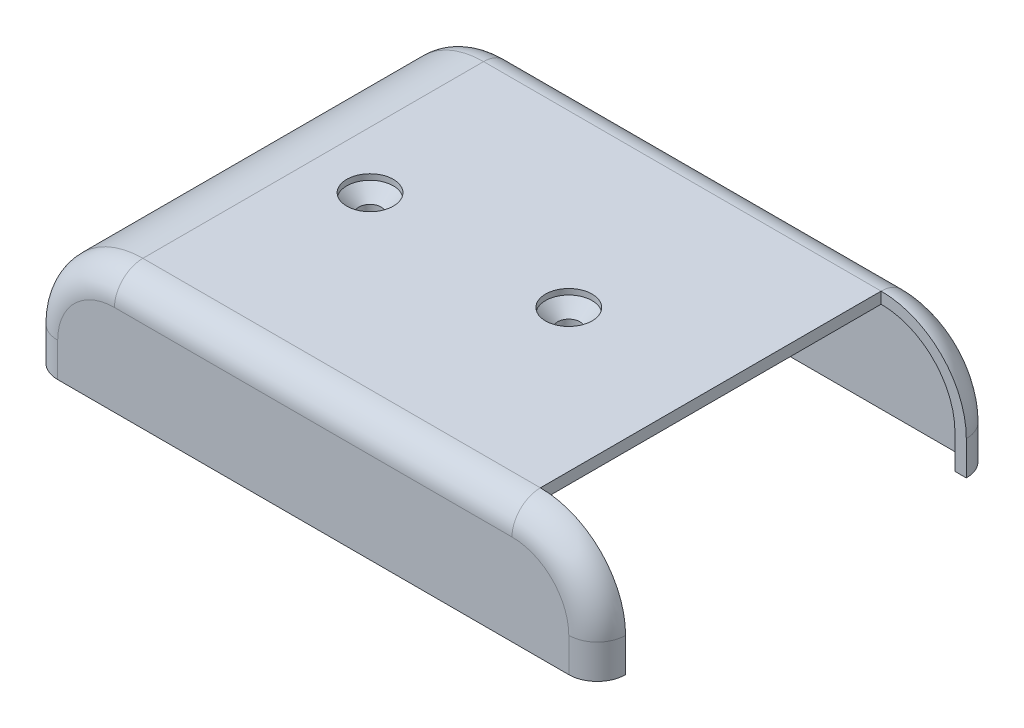
SolidWorks part; units mm, degrees
ref_plane "Front Plane" through (0, 0, 0) normal (0, 0, 1) x (1, 0, 0)
ref_plane "Top Plane" through (0, 0, 0) normal (0, 1, 0) x (1, 0, 0)
ref_plane "Right Plane" through (0, 0, 0) normal (1, 0, 0) x (0, 0, -1)
sketch "Sketch1" plane through (0, 0, 0) normal (0, 1, 0) x (1, 0, 0)
  line L1 (-50, 35) -> (50, 35)
  line L2 (-50, 35) -> (-50, -35)
  line L3 (-50, -35) -> (50, -35)
  line L4 (50, 35) -> (50, -35)
  line L5 (0, -35) -> (0, 35) construction
  line L6 (-50, 0) -> (50, 0) construction
  point P0 (0, 0)
  dimension "D1" = 70
  dimension "D2" = 100
extrude "Boss-Extrude1" add sketch "Sketch1" along normal blind 21
fillet "Fillet1" radius 15 2 edges at (50, 21, 0) (-50, 21, 0)
fillet "Fillet2" radius 5 10 edges at (50, 3, -35) (45.6066, 16.6066, -35) (-50, 3, -35) (-45.6066, 16.6066, -35) (-50, 3, 35) (-45.6066, 16.6066, 35) (50, 3, 35) (45.6066, 16.6066, 35) (0, 21, -35) (0, 21, 35)
shell "Shell1" thickness 2
sketch "Sketch2" plane through (0, 21, 0) normal (0, 1, 0) x (1, 0, 0)
  line L0 (35, 30) -> (35, -30)
  line L1 (35, -30) -> (69.0755, -30)
  line L2 (69.0755, -30) -> (69.0755, 30)
  line L3 (69.0755, 30) -> (35, 30)
extrude "Cut-Extrude1" cut sketch "Sketch2" against normal blind 45
ref_plane "Plane1" through (0, 6, 0) normal (0, 1, 0) x (1, 0, 0)
sketch "Sketch4" plane through (0, 6, 0) normal (0, 1, 0) x (1, 0, 0)
  line L0 (-50, -30) -> (-50, 30) construction
  circle A0 centre (-25, 0) radius 3
  circle A1 centre (10, 0) radius 3
  point P2 (0, 0)
  point P8 (0, 0)
  point P9 (0, 0)
  dimension "D1" = 6
  dimension "D2" = 35
  dimension "D3" = 25
extrude "Boss-Extrude2" add sketch "Sketch4" along normal up to next draft 5 draft outward yes
hole_wizard "CSK for M10 Flat Head Machine Screw4" positions "Sketch12" profile "Sketch13" countersink size "M10" standard "ANSI Metric" end condition up to next
sketch "Sketch12" plane through (0, 21, 0) normal (0, 1, 0) x (1, 0, 0)
  point P0 (-25, 0)
  point P3 (10, 0)
sketch "Sketch13" plane through (-25, 21, 0) normal (1, 0, 0) x (0, 0, 1)
  line L0 (0, 0) -> (0, 15)
  line L1 (0, 15) -> (1.95, 15)
  line L2 (1.95, 15) -> (1.95, 3.15)
  line L3 (1.95, 3.15) -> (4.1, 1)
  line L4 (4.1, 1) -> (4.1, 0)
  line L6 (4.1, 0) -> (0, 0)
  line L7 (-1.95, 3.15) -> (-4.1, 1) construction
  line L11 (0, -6.35) -> (0, 107.95) construction
  dimension "Thru Hole Dia." = 3.9
  dimension "Thru Hole Depth" = 15
  dimension "C'Sink Dia." = 8.2
  dimension "C'Sink Angle" = 90
  dimension "Head Clearance" = 1
